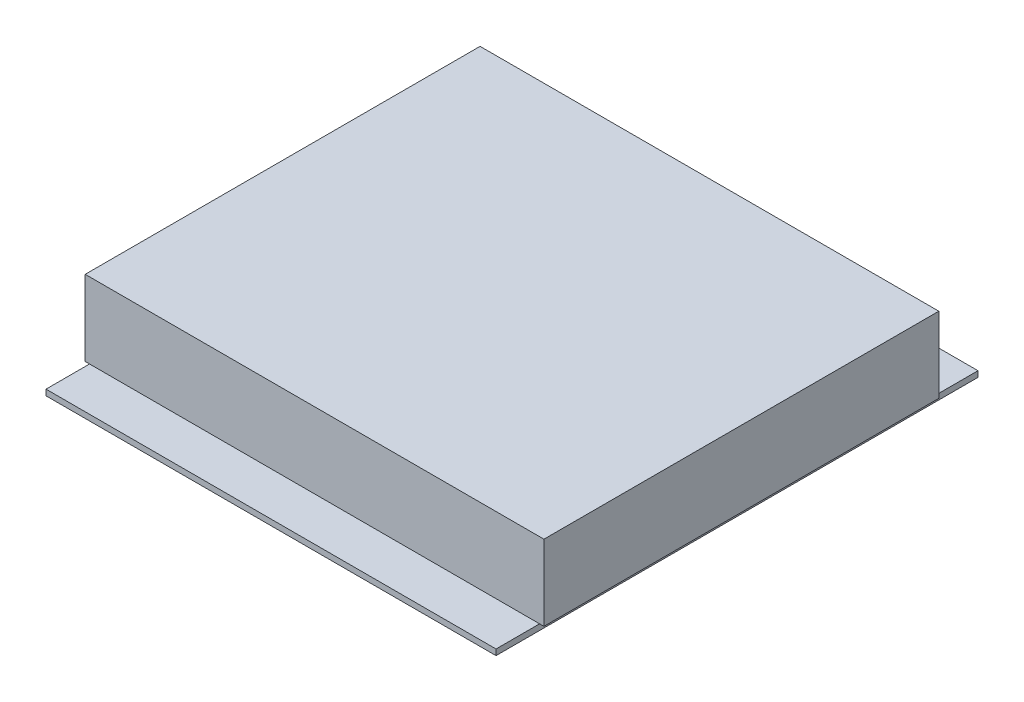
SolidWorks part; units mm, degrees
ref_plane "前视基准面" through (0, 0, 0) normal (0, 0, 1) x (1, 0, 0)
ref_plane "上视基准面" through (0, 0, 0) normal (0, 1, 0) x (1, 0, 0)
ref_plane "右视基准面" through (0, 0, 0) normal (1, 0, 0) x (0, 0, -1)
sketch "草图1" plane through (0, 0, 0) normal (0, 1, 0) x (1, 0, 0)
  line L0 (0, 119.6086) -> (0, -106.3438) construction
  line L1 (-79, 68) -> (79, 68)
  line L2 (-79, 68) -> (-79, -68)
  line L3 (-79, -68) -> (79, -68)
  line L4 (79, 68) -> (79, -68)
  line L5 (-120.2285, 0) -> (112.3847, 0) construction
  dimension "D1" = 158
  dimension "D2" = 136
extrude "拉伸1" add sketch "草图1" along normal blind 26
sketch "草图2" plane through (0, 0, 0) normal (0, -1, 0) x (1, 0, 0)
  line L0 (-79, 68) -> (79, 68) construction
  line L1 (-77.5, 83) -> (77.5, 83)
  line L2 (-77.5, 83) -> (-77.5, -83)
  line L3 (-77.5, -83) -> (77.5, -83)
  line L4 (77.5, 83) -> (77.5, -83)
  line L5 (79, -68) -> (-79, -68) construction
  line L6 (-79, -68) -> (-79, 68) construction
  line L7 (79, 68) -> (79, -68) construction
  dimension "D1" = 15
  dimension "D2" = 15
  dimension "D3" = 1.5
  dimension "D4" = 1.5
extrude "拉伸2" add sketch "草图2" along normal blind 2
